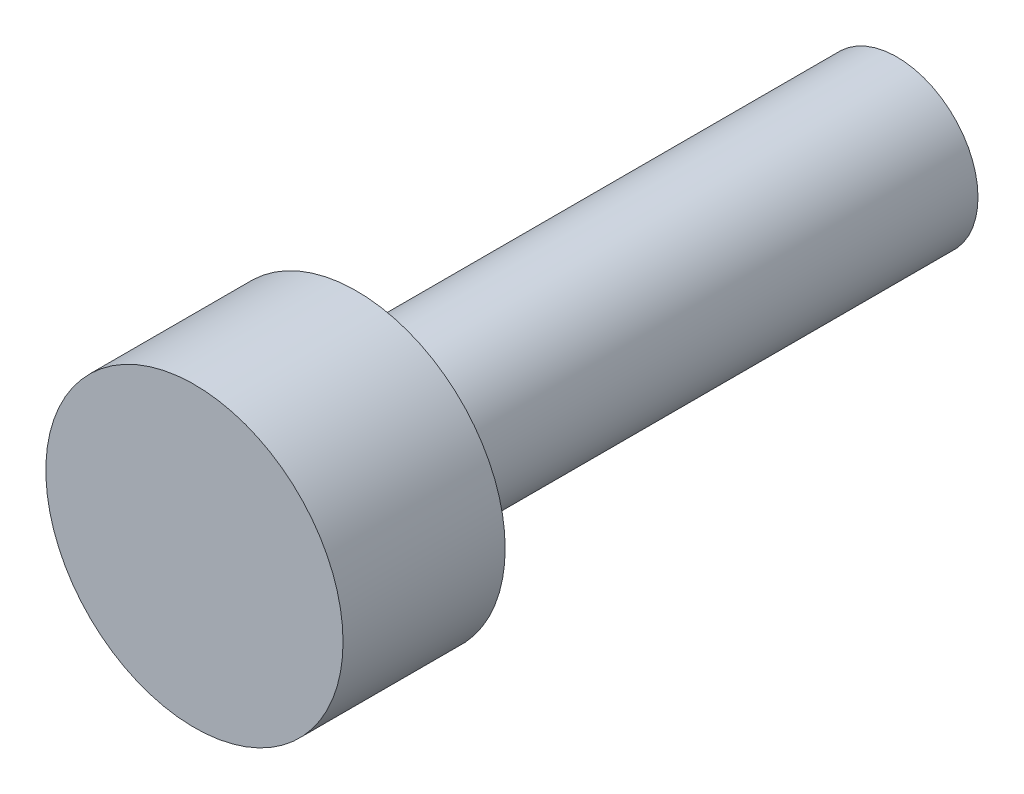
SolidWorks part; units mm, degrees
ref_plane "Front Plane" through (0, 0, 0) normal (0, 0, 1) x (1, 0, 0)
ref_plane "Top Plane" through (0, 0, 0) normal (0, 1, 0) x (1, 0, 0)
ref_plane "Right Plane" through (0, 0, 0) normal (1, 0, 0) x (0, 0, -1)
sketch "Sketch1" plane through (0, 0, 0) normal (0, 0, 1) x (1, 0, 0)
  circle A0 centre (0, 0) radius 1.5
  dimension "D1" = 3
extrude "Boss-Extrude1" add sketch "Sketch1" along normal blind 10
sketch "Sketch2" plane through (0, 0, 10) normal (0, 0, 1) x (1, 0, 0)
  circle A0 centre (0, 0) radius 2.75
  dimension "D1" = 5.5
extrude "Boss-Extrude2" add sketch "Sketch2" along normal blind 3
